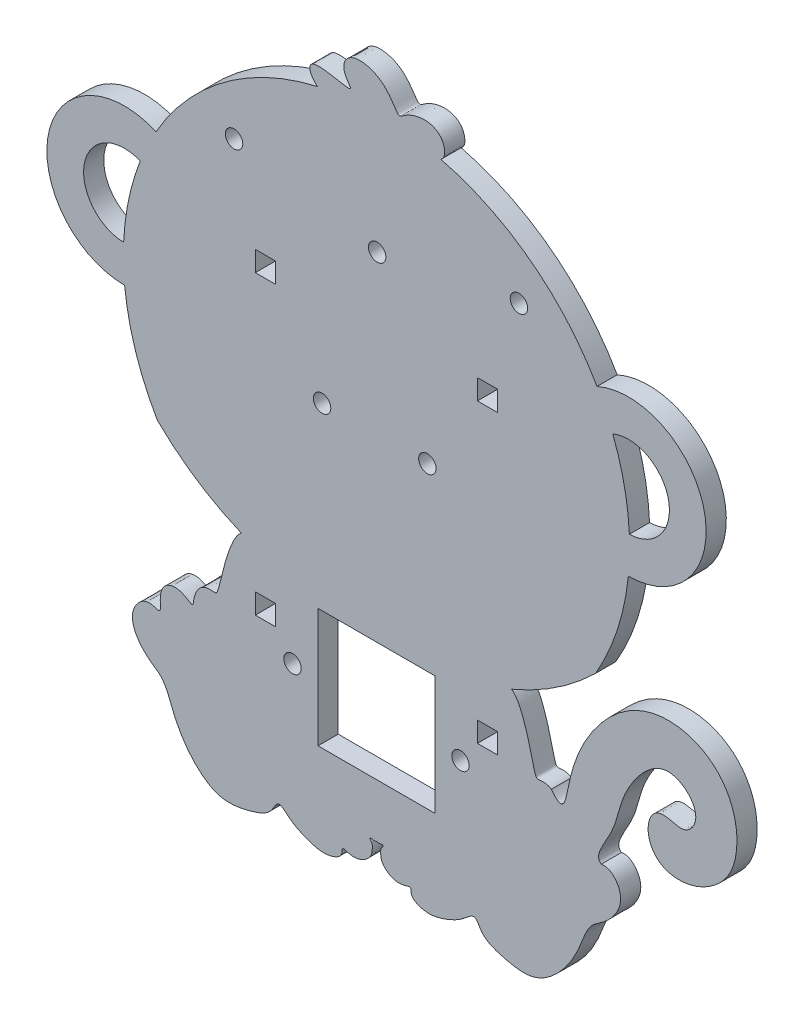
SolidWorks part; units mm, degrees
ref_plane "Front Plane" through (0, 0, 0) normal (0, 0, 1) x (1, 0, 0)
ref_plane "Top Plane" through (0, 0, 0) normal (0, 1, 0) x (1, 0, 0)
ref_plane "Right Plane" through (0, 0, 0) normal (1, 0, 0) x (0, 0, -1)
sketch "Model" plane through (0, 0, 0) normal (0, 0, 1) x (1, 0, 0)
  line L0 (-354.7776, 349.4226) -> (-354.7776, 392.0292) construction
  line L1 (-368.5276, 390.0292) -> (-368.5276, 362.0292)
  line L2 (-368.5276, 390.0292) -> (-341.0276, 390.0292)
  line L21 (-354.7776, 390.0292) -> (-354.7776, 362.0292)
  line L26 (-368.5276, 362.0292) -> (-341.0276, 362.0292)
  line L27 (-341.0276, 390.0292) -> (-341.0276, 362.0292)
  line L28 (-378.5276, 381.2792) -> (-383.2776, 381.2792)
  line L29 (-331.0276, 386.0292) -> (-326.2776, 386.0292)
  line L30 (-331.0276, 386.0292) -> (-331.0276, 381.2792)
  line L31 (-331.0276, 381.2792) -> (-326.2776, 381.2792)
  line L32 (-326.2776, 386.0292) -> (-326.2776, 381.2792)
  line L33 (-383.2776, 386.0292) -> (-383.2776, 381.2792)
  line L34 (-378.5276, 386.0292) -> (-383.2776, 386.0292)
  line L35 (-378.5276, 386.0292) -> (-378.5276, 381.2792)
  line L36 (-326.2776, 451.0292) -> (-331.0276, 451.0292) construction
  line L37 (-326.2776, 455.7792) -> (-326.2776, 451.0292) construction
  line L38 (-331.0276, 455.7792) -> (-331.0276, 451.0292) construction
  line L39 (-326.2776, 455.7792) -> (-331.0276, 455.7792) construction
  line L40 (-383.2776, 451.0292) -> (-378.5276, 451.0292) construction
  line L41 (-383.2776, 455.7792) -> (-383.2776, 451.0292) construction
  line L42 (-378.5276, 455.7792) -> (-378.5276, 451.0292) construction
  line L43 (-383.2776, 455.7792) -> (-378.5276, 455.7792) construction
  line L44 (-326.2776, 451.0292) -> (-331.0276, 451.0292)
  line L45 (-326.2776, 455.7792) -> (-326.2776, 451.0292)
  line L46 (-331.0276, 455.7792) -> (-331.0276, 451.0292)
  line L47 (-326.2776, 455.7792) -> (-331.0276, 455.7792)
  line L48 (-383.2776, 451.0292) -> (-378.5276, 451.0292)
  line L49 (-383.2776, 455.7792) -> (-383.2776, 451.0292)
  line L50 (-378.5276, 455.7792) -> (-378.5276, 451.0292)
  line L51 (-383.2776, 455.7792) -> (-378.5276, 455.7792)
  line L52 (-397.2776, 416.2792) -> (-402.0276, 416.2792) construction
  line L53 (-312.2776, 421.0292) -> (-307.5276, 421.0292) construction
  line L54 (-312.2776, 421.0292) -> (-312.2776, 416.2792) construction
  line L55 (-312.2776, 416.2792) -> (-307.5276, 416.2792) construction
  line L56 (-307.5276, 421.0292) -> (-307.5276, 416.2792) construction
  line L57 (-402.0276, 421.0292) -> (-402.0276, 416.2792) construction
  line L58 (-397.2776, 421.0292) -> (-402.0276, 421.0292) construction
  line L59 (-397.2776, 421.0292) -> (-397.2776, 416.2792) construction
  circle A0 centre (-295.506, 451.3512) radius 18.2563
  circle A1 centre (-295.506, 451.3512) radius 9.6191
  circle A2 centre (-414.0491, 451.3512) radius 9.6191
  circle A3 centre (-414.0491, 451.3512) radius 18.2562
  arc A4 (-354.7776, 392.0292) -> (-303.2483, 409.4214) centre (-346.9752, 453.9435) ccw
  arc A5 (-303.2483, 409.4214) -> (-354.7776, 497.7106) centre (-353.9365, 439.0196) ccw
  arc A6 (-354.7776, 497.7106) -> (-406.3069, 409.4214) centre (-355.6187, 439.0196) ccw
  arc A7 (-406.3069, 409.4214) -> (-354.7776, 392.0292) centre (-362.58, 453.9435) ccw
  circle A17 centre (-388.2776, 475.7792) radius 2.05
  circle A18 centre (-321.2776, 475.7792) radius 2.05
  circle A19 centre (-374.5276, 375.7792) radius 2.05
  circle A20 centre (-335.0276, 375.7792) radius 2.05
  circle A24 centre (-342.8132, 432.3712) radius 1.7
  circle A25 centre (-367.5781, 432.2899) radius 1.7
  circle A26 centre (-354.6192, 469.5436) radius 1.7
  circle A27 centre (-367.5781, 432.2899) radius 2.05
  circle A28 centre (-342.8132, 432.3712) radius 2.05
  circle A29 centre (-354.6192, 469.5436) radius 2.05
  spline S0 degree 5 poles (-386.5513, 396.3273) (-386.9161, 396.0792) (-387.366, 395.6344) (-387.8968, 394.8986) (-388.5033, 393.7572) (-389.1715, 392.131) (-389.5779, 391.0147) (-389.9703, 389.8193) (-390.4193, 388.3234) (-390.8333, 386.8049) (-391.2016, 385.3464) (-391.5167, 384.0353) (-391.7817, 382.9443) (-391.9754, 382.2094) (-392.154, 381.6648) (-392.3367, 381.3111) (-392.5515, 381.1299) (-392.8335, 381.0822) (-393.2115, 381.1155) (-393.6934, 381.1695) (-394.2612, 381.1826) (-394.881, 381.0994) (-395.5104, 380.8776) (-396.1059, 380.4945) (-396.6315, 379.9559) (-397.064, 379.2975) (-397.3921, 378.574) (-397.6173, 377.8496) (-397.7535, 377.1888) (-397.8274, 376.647) (-397.8791, 376.2603) (-397.9596, 376.0385) (-398.1148, 375.9725) (-398.366, 376.0408) (-398.7069, 376.2147) (-399.1201, 376.4601) (-399.5915, 376.7412) (-400.118, 377.0223) (-400.6998, 377.2689) (-401.4638, 377.484) (-402.3002, 377.5538) (-403.1741, 377.4267) (-404.0022, 377.0659) (-404.6982, 376.4644) (-405.1535, 375.8118) (-405.4613, 375.0322) (-405.6199, 374.1669) (-405.658, 373.2789) (-405.6265, 372.4425) (-405.5875, 371.7311) (-405.6037, 371.2053) (-405.7274, 370.9008) (-405.9901, 370.8167) (-406.3911, 370.9021) (-406.9056, 371.0748) (-407.4962, 371.2433) (-408.1222, 371.3275) (-408.7511, 371.2827) (-409.3596, 371.0975) (-409.9312, 370.7828) (-410.4544, 370.3635) (-410.9212, 369.8697) (-411.3251, 369.3269) (-411.6596, 368.7503) (-411.9191, 368.1478) (-412.0987, 367.5224) (-412.1944, 366.8744) (-412.2033, 366.204) (-412.0922, 365.2374) (-411.7958, 364.2405) (-411.2536, 363.0979) (-410.5055, 362.004) (-409.6286, 361.0209) (-408.9407, 360.363) (-408.2617, 359.7955) (-407.7193, 359.3836) (-407.2138, 359.0282) (-406.7532, 358.7179) (-406.3372, 358.4326) (-405.9584, 358.1461) (-405.6064, 357.8322) (-405.2709, 357.469) (-404.9452, 357.0452) (-404.6288, 356.5637) (-404.3252, 356.0366) (-404.0394, 355.4808) (-403.7755, 354.9137) (-403.4863, 354.2349) (-403.2244, 353.5638) (-402.972, 352.8931) (-402.7045, 352.203) (-402.4017, 351.478) (-402.0626, 350.7211) (-401.6746, 349.928) (-401.239, 349.111) (-400.7631, 348.2898) (-400.2543, 347.482) (-399.7226, 346.693) (-399.1634, 345.9321) (-398.5743, 345.1992) (-397.9495, 344.4888) (-397.2819, 343.7971) (-396.6937, 343.2329) (-395.9467, 342.5739) (-395.1459, 341.9478) (-394.2909, 341.3752) (-393.3842, 340.8821) (-392.43, 340.4917) (-391.606, 340.244) (-390.756, 340.0794) (-389.8831, 339.9983) (-388.9906, 339.995) (-388.0822, 340.0607) (-387.1626, 340.184) (-386.2377, 340.3533) (-385.315, 340.5579) (-384.404, 340.7898) (-383.5163, 341.0454) (-382.6665, 341.327) (-381.8713, 341.6429) (-381.1468, 342.0028) (-380.5061, 342.4143) (-379.9577, 342.8796) (-379.5022, 343.3918) (-379.1308, 343.9312) (-378.8219, 344.461) (-378.5447, 344.9321) (-378.2678, 345.2959) (-377.9655, 345.5144) (-377.6259, 345.571) (-377.2571, 345.4813) (-376.8758, 345.2788) (-376.4963, 345.0025) (-376.1171, 344.6823) (-375.7208, 344.3352) (-375.2832, 343.9706) (-374.7791, 343.5936) (-374.1903, 343.2075) (-373.3777, 342.7411) (-372.4498, 342.2849) (-371.4489, 341.8618) (-370.4344, 341.4969) (-369.4571, 341.2116) (-368.6859, 341.0352) (-367.9644, 340.9249) (-367.2855, 340.8811) (-366.6359, 340.9021) (-366.0015, 340.9842) (-365.3739, 341.1239) (-364.7563, 341.3185) (-364.1709, 341.5681) (-363.6579, 341.8743) (-363.2584, 342.2351) (-362.9996, 342.6398) (-362.8828, 343.0653) (-362.8624, 343.4679) (-362.8603, 343.7943) (-362.8008, 344.002) (-362.6453, 344.0822) (-362.4039, 344.0645) (-362.091, 343.9838) (-361.7122, 343.8689) (-361.2711, 343.747) (-360.7722, 343.6434) (-360.2251, 343.5846) (-359.6439, 343.594) (-359.0456, 343.6889) (-358.3311, 343.9146) (-357.653, 344.2718) (-357.0557, 344.716) (-356.5775, 345.1787) (-356.2334, 345.621) (-356.0331, 345.9754) (-355.9027, 346.3429) (-355.8208, 346.7573) (-355.7698, 347.2366) (-355.7451, 347.7596) (-355.7624, 348.2488) (-355.8386, 348.6234) (-355.9777, 348.8376) (-356.1508, 348.9418) (-356.2927, 349.0757) (-356.3365, 349.2881) (-356.2363, 349.4431) (-355.9971, 349.4554) (-355.6775, 349.3823) (-355.3456, 349.3188) (-355.1001, 349.3199) (-354.9324, 349.357) (-354.828, 349.398) (-354.7776, 349.4226) knots 0 0 0 0 0 0 0.02 0.025 0.03 0.035 0.04 0.045 0.05 0.06 0.065 0.07 0.075 0.08 0.085 0.09 0.095 0.1 0.105 0.11 0.115 0.12 0.125 0.13 0.135 0.14 0.145 0.15 0.155 0.16 0.165 0.17 0.175 0.18 0.185 0.19 0.195 0.2 0.205 0.21 0.22 0.225 0.23 0.235 0.24 0.245 0.25 0.255 0.26 0.265 0.27 0.275 0.28 0.285 0.29 0.295 0.3 0.305 0.31 0.315 0.32 0.325 0.33 0.335 0.34 0.345 0.35 0.355 0.36 0.375 0.38 0.39 0.395 0.4 0.405 0.41 0.415 0.42 0.425 0.43 0.435 0.44 0.445 0.45 0.455 0.46 0.465 0.47 0.48 0.485 0.49 0.495 0.5 0.51 0.515 0.52 0.525 0.53 0.54 0.545 0.55 0.555 0.56 0.565 0.575 0.58 0.585 0.59 0.595 0.6 0.605 0.61 0.615 0.62 0.625 0.63 0.635 0.64 0.645 0.65 0.655 0.66 0.665 0.67 0.675 0.68 0.685 0.69 0.695 0.7 0.705 0.71 0.715 0.72 0.725 0.73 0.735 0.74 0.745 0.755 0.76 0.765 0.77 0.775 0.78 0.785 0.79 0.795 0.8 0.805 0.81 0.815 0.82 0.825 0.83 0.835 0.84 0.845 0.85 0.855 0.86 0.865 0.87 0.875 0.88 0.885 0.89 0.895 0.905 0.91 0.915 0.92 0.925 0.93 0.935 0.94 0.945 0.95 0.955 0.96 0.965 0.97 0.975 0.98 0.985 0.99 0.995 1 1 1 1 1 1 weights 1 1 1 1 1 1 1 1 1 1 1 1 1 1 1 1 1 1 1 1 1 1 1 1 1 1 1 1 1 1 1 1 1 1 1 1 1 1 1 1 1 1 1 1 1 1 1 1 1 1 1 1 1 1 1 1 1 1 1 1 1 1 1 1 1 1 1 1 1 1 1 1 1 1 1 1 1 1 1 1 1 1 1 1 1 1 1 1 1 1 1 1 1 1 1 1 1 1 1 1 1 1 1 1 1 1 1 1 1 1 1 1 1 1 1 1 1 1 1 1 1 1 1 1 1 1 1 1 1 1 1 1 1 1 1 1 1 1 1 1 1 1 1 1 1 1 1 1 1 1 1 1 1 1 1 1 1 1 1 1 1 1 1 1 1 1 1 1 1 1 1 1 1 1 1 1 1 1 1 1 1 1 1 1 1 1 1 1 1 1 1
  spline S1 degree 5 poles (-323.0039, 396.3273) (-322.6391, 396.0792) (-322.1892, 395.6344) (-321.6584, 394.8986) (-321.0519, 393.7572) (-320.3837, 392.131) (-319.9773, 391.0147) (-319.5849, 389.8193) (-319.1359, 388.3234) (-318.7219, 386.8049) (-318.3536, 385.3464) (-318.0385, 384.0353) (-317.7735, 382.9443) (-317.5798, 382.2094) (-317.4012, 381.6648) (-317.2185, 381.3111) (-317.0037, 381.1299) (-316.7217, 381.0822) (-316.3437, 381.1155) (-315.8618, 381.1695) (-315.294, 381.1826) (-314.6741, 381.0994) (-314.0448, 380.8776) (-313.4493, 380.4945) (-312.9237, 379.9559) (-312.4912, 379.2975) (-312.1631, 378.574) (-311.9379, 377.8496) (-311.8017, 377.1888) (-311.7278, 376.647) (-311.6761, 376.2603) (-311.5956, 376.0385) (-311.4404, 375.9725) (-311.1892, 376.0408) (-310.8483, 376.2147) (-310.4351, 376.4601) (-309.9637, 376.7412) (-309.4372, 377.0223) (-308.8554, 377.2689) (-308.0914, 377.484) (-307.2549, 377.5538) (-306.3811, 377.4267) (-305.553, 377.0659) (-304.857, 376.4644) (-304.4017, 375.8118) (-304.0939, 375.0322) (-303.9353, 374.1669) (-303.8972, 373.2789) (-303.9287, 372.4425) (-303.9677, 371.7311) (-303.9515, 371.2053) (-303.8278, 370.9008) (-303.5651, 370.8167) (-303.1641, 370.9021) (-302.6496, 371.0748) (-302.0589, 371.2433) (-301.433, 371.3275) (-300.8041, 371.2827) (-300.1956, 371.0975) (-299.624, 370.7828) (-299.1008, 370.3635) (-298.634, 369.8697) (-298.2301, 369.3269) (-297.8956, 368.7503) (-297.6361, 368.1478) (-297.4565, 367.5224) (-297.3608, 366.8744) (-297.3519, 366.204) (-297.463, 365.2374) (-297.7594, 364.2405) (-298.3016, 363.0979) (-299.0496, 362.004) (-299.9266, 361.0209) (-300.6145, 360.363) (-301.2935, 359.7955) (-301.8359, 359.3836) (-302.3414, 359.0282) (-302.8019, 358.7179) (-303.218, 358.4326) (-303.5968, 358.1461) (-303.9488, 357.8322) (-304.2843, 357.469) (-304.61, 357.0452) (-304.9264, 356.5637) (-305.23, 356.0366) (-305.5158, 355.4808) (-305.7797, 354.9137) (-306.0689, 354.2349) (-306.3308, 353.5638) (-306.5832, 352.8931) (-306.8507, 352.203) (-307.1535, 351.478) (-307.4926, 350.7211) (-307.8805, 349.928) (-308.3162, 349.111) (-308.7921, 348.2898) (-309.3008, 347.482) (-309.8326, 346.693) (-310.3918, 345.9321) (-310.9809, 345.1992) (-311.6057, 344.4888) (-312.2733, 343.7971) (-312.8615, 343.2329) (-313.6085, 342.5739) (-314.4093, 341.9478) (-315.2643, 341.3752) (-316.171, 340.8821) (-317.1251, 340.4917) (-317.9492, 340.244) (-318.7992, 340.0794) (-319.6721, 339.9983) (-320.5646, 339.995) (-321.473, 340.0607) (-322.3926, 340.184) (-323.3175, 340.3533) (-324.2402, 340.5579) (-325.1512, 340.7898) (-326.0389, 341.0454) (-326.8887, 341.327) (-327.6839, 341.6429) (-328.4084, 342.0028) (-329.049, 342.4143) (-329.5975, 342.8796) (-330.053, 343.3918) (-330.4244, 343.9312) (-330.7333, 344.461) (-331.0105, 344.9321) (-331.2874, 345.2959) (-331.5897, 345.5144) (-331.9293, 345.571) (-332.298, 345.4813) (-332.6794, 345.2788) (-333.0589, 345.0025) (-333.4381, 344.6823) (-333.8343, 344.3352) (-334.272, 343.9706) (-334.7761, 343.5936) (-335.3649, 343.2075) (-336.1775, 342.7411) (-337.1053, 342.2849) (-338.1063, 341.8618) (-339.1207, 341.4969) (-340.0981, 341.2116) (-340.8693, 341.0352) (-341.5908, 340.9249) (-342.2697, 340.8811) (-342.9193, 340.9021) (-343.5537, 340.9842) (-344.1813, 341.1239) (-344.7989, 341.3185) (-345.3842, 341.5681) (-345.8972, 341.8743) (-346.2968, 342.2351) (-346.5556, 342.6398) (-346.6724, 343.0653) (-346.6928, 343.4679) (-346.6949, 343.7943) (-346.7544, 344.002) (-346.9099, 344.0822) (-347.1513, 344.0645) (-347.4642, 343.9838) (-347.843, 343.8689) (-348.2841, 343.747) (-348.783, 343.6434) (-349.33, 343.5846) (-349.9113, 343.594) (-350.5096, 343.6889) (-351.2241, 343.9146) (-351.9022, 344.2718) (-352.4995, 344.716) (-352.9777, 345.1787) (-353.3218, 345.621) (-353.5221, 345.9754) (-353.6525, 346.3429) (-353.7344, 346.7573) (-353.7854, 347.2366) (-353.8101, 347.7596) (-353.7928, 348.2488) (-353.7166, 348.6234) (-353.5775, 348.8376) (-353.4043, 348.9418) (-353.2625, 349.0757) (-353.2187, 349.2881) (-353.3188, 349.4431) (-353.5581, 349.4554) (-353.8776, 349.3823) (-354.2096, 349.3188) (-354.4551, 349.3199) (-354.6228, 349.357) (-354.7272, 349.398) (-354.7776, 349.4226) knots 0 0 0 0 0 0 0.02 0.025 0.03 0.035 0.04 0.045 0.05 0.06 0.065 0.07 0.075 0.08 0.085 0.09 0.095 0.1 0.105 0.11 0.115 0.12 0.125 0.13 0.135 0.14 0.145 0.15 0.155 0.16 0.165 0.17 0.175 0.18 0.185 0.19 0.195 0.2 0.205 0.21 0.22 0.225 0.23 0.235 0.24 0.245 0.25 0.255 0.26 0.265 0.27 0.275 0.28 0.285 0.29 0.295 0.3 0.305 0.31 0.315 0.32 0.325 0.33 0.335 0.34 0.345 0.35 0.355 0.36 0.375 0.38 0.39 0.395 0.4 0.405 0.41 0.415 0.42 0.425 0.43 0.435 0.44 0.445 0.45 0.455 0.46 0.465 0.47 0.48 0.485 0.49 0.495 0.5 0.51 0.515 0.52 0.525 0.53 0.54 0.545 0.55 0.555 0.56 0.565 0.575 0.58 0.585 0.59 0.595 0.6 0.605 0.61 0.615 0.62 0.625 0.63 0.635 0.64 0.645 0.65 0.655 0.66 0.665 0.67 0.675 0.68 0.685 0.69 0.695 0.7 0.705 0.71 0.715 0.72 0.725 0.73 0.735 0.74 0.745 0.755 0.76 0.765 0.77 0.775 0.78 0.785 0.79 0.795 0.8 0.805 0.81 0.815 0.82 0.825 0.83 0.835 0.84 0.845 0.85 0.855 0.86 0.865 0.87 0.875 0.88 0.885 0.89 0.895 0.905 0.91 0.915 0.92 0.925 0.93 0.935 0.94 0.945 0.95 0.955 0.96 0.965 0.97 0.975 0.98 0.985 0.99 0.995 1 1 1 1 1 1 weights 1 1 1 1 1 1 1 1 1 1 1 1 1 1 1 1 1 1 1 1 1 1 1 1 1 1 1 1 1 1 1 1 1 1 1 1 1 1 1 1 1 1 1 1 1 1 1 1 1 1 1 1 1 1 1 1 1 1 1 1 1 1 1 1 1 1 1 1 1 1 1 1 1 1 1 1 1 1 1 1 1 1 1 1 1 1 1 1 1 1 1 1 1 1 1 1 1 1 1 1 1 1 1 1 1 1 1 1 1 1 1 1 1 1 1 1 1 1 1 1 1 1 1 1 1 1 1 1 1 1 1 1 1 1 1 1 1 1 1 1 1 1 1 1 1 1 1 1 1 1 1 1 1 1 1 1 1 1 1 1 1 1 1 1 1 1 1 1 1 1 1 1 1 1 1 1 1 1 1 1 1 1 1 1 1 1 1 1 1 1 1
  spline S2 degree 5 poles (-313.6608, 380.6036) (-313.4447, 380.3201) (-313.0302, 379.8091) (-312.4617, 379.2104) (-311.8099, 378.7481) (-311.1658, 378.7209) (-310.6734, 379.2168) (-310.2927, 380.1782) (-309.9686, 381.5239) (-309.6406, 383.1622) (-309.2509, 385.0015) (-308.7553, 386.9633) (-308.0017, 389.3938) (-307.0301, 391.8531) (-305.8363, 394.2764) (-304.438, 396.6235) (-302.856, 398.8596) (-301.4232, 400.6299) (-299.5708, 402.6142) (-297.5538, 404.3848) (-295.3743, 405.8881) (-292.6508, 407.2693) (-289.33, 408.2696) (-286.299, 408.5941) (-283.2651, 408.3445) (-280.3791, 407.5391) (-278.0928, 406.4785) (-276.3489, 405.3668) (-274.4851, 403.7878) (-272.9371, 401.946) (-271.7278, 399.9069) (-270.8571, 397.7451) (-270.3065, 395.5388) (-270.0462, 393.71) (-269.965, 391.9301) (-270.041, 390.2346) (-270.2523, 388.6524) (-270.5799, 387.2019) (-271.0097, 385.8888) (-271.5359, 384.701) (-272.1612, 383.6109) (-272.8958, 382.5869) (-273.7555, 381.6014) (-274.7609, 380.6417) (-275.9355, 379.7174) (-277.2973, 378.8569) (-278.8515, 378.1044) (-280.5823, 377.5164) (-282.4459, 377.1586) (-284.3607, 377.1036) (-286.2191, 377.417) (-287.9032, 378.1427) (-289.299, 379.2867) (-290.311, 380.8037) (-290.8776, 382.5789) (-290.9832, 384.4209) (-290.6506, 386.112) (-289.936, 387.4514) (-288.9223, 388.2997) (-287.7148, 388.6275) (-286.4328, 388.5495) (-285.1876, 388.2576) (-284.0619, 387.9667) (-283.0865, 387.8525) (-282.2242, 388) (-281.4248, 388.4326) (-280.673, 389.1343) (-280.0427, 390.0762) (-279.6515, 391.2145) (-279.6146, 392.4895) (-279.9934, 393.8227) (-280.764, 395.118) (-281.8511, 396.2738) (-283.152, 397.1938) (-284.5629, 397.798) (-286.0086, 398.0348) (-287.4505, 397.8849) (-288.8706, 397.3556) (-290.2614, 396.4772) (-291.6143, 395.2987) (-292.9061, 393.8845) (-294.101, 392.3076) (-295.162, 390.6429) (-296.0582, 388.9596) (-296.775, 387.314) (-297.3214, 385.7431) (-297.7428, 384.2552) (-298.1147, 382.8324) (-298.5188, 381.4451) (-299.0233, 380.0639) (-299.6638, 378.6704) (-300.4174, 377.2729) (-301.2032, 375.907) (-301.9108, 374.6227) (-302.4229, 373.4731) (-302.6383, 372.5046) (-302.5279, 371.8953) (-302.2784, 371.535) (-302.0378, 371.3378) (-301.8989, 371.25) knots 0 0 0 0 0 0 0.01 0.02 0.03 0.04 0.05 0.06 0.07 0.08 0.09 0.1 0.11 0.13 0.14 0.15 0.16 0.17 0.18 0.2 0.21 0.22 0.24 0.26 0.27 0.28 0.29 0.3 0.31 0.33 0.34 0.35 0.36 0.37 0.38 0.39 0.4 0.41 0.42 0.43 0.44 0.45 0.46 0.47 0.48 0.49 0.5 0.51 0.52 0.53 0.54 0.55 0.56 0.57 0.58 0.59 0.6 0.61 0.62 0.63 0.64 0.65 0.66 0.67 0.68 0.69 0.7 0.71 0.72 0.73 0.74 0.75 0.76 0.77 0.78 0.79 0.8 0.81 0.82 0.83 0.84 0.85 0.86 0.87 0.88 0.89 0.9 0.91 0.92 0.93 0.94 0.95 0.96 0.97 0.98 0.99 1 1 1 1 1 1 weights 1 1 1 1 1 1 1 1 1 1 1 1 1 1 1 1 1 1 1 1 1 1 1 1 1 1 1 1 1 1 1 1 1 1 1 1 1 1 1 1 1 1 1 1 1 1 1 1 1 1 1 1 1 1 1 1 1 1 1 1 1 1 1 1 1 1 1 1 1 1 1 1 1 1 1 1 1 1 1 1 1 1 1 1 1 1 1 1 1 1 1 1 1 1 1 1 1 1 1 1
  spline S3 degree 5 poles (-368.6485, 496.2522) (-368.7445, 496.3189) (-368.9332, 496.4614) (-369.2068, 496.7025) (-369.5526, 497.079) (-369.9454, 497.6352) (-370.274, 498.2589) (-370.4903, 498.915) (-370.5107, 499.5416) (-370.2384, 500.0643) (-369.5991, 500.4175) (-368.5716, 500.5624) (-367.2236, 500.5088) (-365.6871, 500.3043) (-364.1304, 500.0214) (-362.7304, 499.745) (-361.6458, 499.5606) (-360.9878, 499.5411) (-360.7964, 499.7361) (-361.0037, 500.1558) (-361.4562, 500.7754) (-361.9696, 501.5464) (-362.3683, 502.407) (-362.5408, 503.2925) (-362.4544, 504.1433) (-362.127, 504.907) (-361.609, 505.5429) (-360.9624, 506.0248) (-360.2377, 506.3463) (-359.4651, 506.519) (-358.6621, 506.5638) (-357.8368, 506.5034) (-356.9934, 506.3554) (-356.1367, 506.1232) (-355.2752, 505.7947) (-354.4199, 505.3529) (-353.5839, 504.7839) (-352.7824, 504.0858) (-352.0321, 503.2767) (-351.3511, 502.4053) (-350.7568, 501.5504) (-350.2591, 500.8009) (-349.8549, 500.2405) (-349.5224, 499.9306) (-349.215, 499.8941) (-348.8555, 500.0985) (-348.3621, 500.4755) (-347.6717, 500.9383) (-346.77, 501.4022) (-345.6888, 501.7923) (-344.4899, 502.0451) (-343.2539, 502.1125) (-342.0666, 501.9648) (-341.0067, 501.594) (-340.1326, 501.0174) (-339.4704, 500.2805) (-339.0219, 499.4471) (-338.7725, 498.5899) (-338.6988, 497.7804) (-338.776, 497.0807) (-338.9866, 496.5313) (-339.2553, 496.2274) (-339.5119, 496.0787) (-339.7073, 496.0148) (-339.8111, 495.9917) knots 0 0 0 0 0 0 0.016667 0.033333 0.05 0.066667 0.083333 0.1 0.116667 0.133333 0.15 0.166667 0.183333 0.2 0.216667 0.233333 0.25 0.266667 0.283333 0.3 0.316667 0.333333 0.35 0.366667 0.383333 0.4 0.416667 0.433333 0.45 0.466667 0.483333 0.5 0.516667 0.533333 0.55 0.566667 0.583333 0.6 0.616667 0.633333 0.65 0.666667 0.683333 0.7 0.716667 0.733333 0.75 0.766667 0.783333 0.8 0.816667 0.833333 0.85 0.866667 0.883333 0.9 0.916667 0.933333 0.95 0.966667 0.983333 1 1 1 1 1 1 weights 1 1 1 1 1 1 1 1 1 1 1 1 1 1 1 1 1 1 1 1 1 1 1 1 1 1 1 1 1 1 1 1 1 1 1 1 1 1 1 1 1 1 1 1 1 1 1 1 1 1 1 1 1 1 1 1 1 1 1 1 1 1 1 1 1
  dimension "D10" = 4.1
  dimension "D12" = 20
  dimension "D15" = 4.1
  dimension "D4" = 4.1
  dimension "D5" = 4.1
  dimension "D6" = 4.1
  dimension "D2" = 13.75
  dimension "D3" = 2
  dimension "D1" = 28
  dimension "D7" = 4.75
  dimension "D8" = 4
  dimension "D9" = 10
  dimension "D11" = 5
  dimension "D13" = 30
  dimension "D14" = 14
  dimension "D16" = 5.5
  dimension "D17" = 4
extrude "Boss-Extrude1" add sketch "Model" along normal blind 4.75
